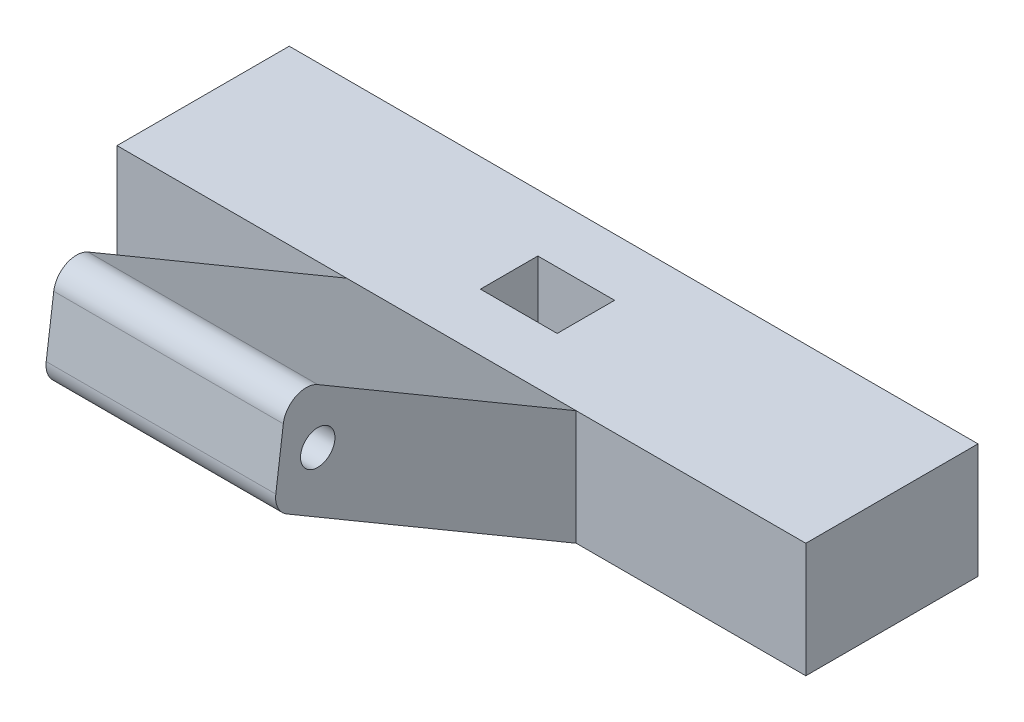
SolidWorks part; units mm, degrees
ref_plane "Plan de face" through (0, 0, 0) normal (0, 0, 1) x (1, 0, 0)
ref_plane "Plan de dessus" through (0, 0, 0) normal (0, 1, 0) x (1, 0, 0)
ref_plane "Plan de droite" through (0, 0, 0) normal (1, 0, 0) x (0, 0, -1)
sketch "Esquisse1" plane through (0, 0, 0) normal (0, 1, 0) x (1, 0, 0)
  line L6 (-30, -7.5) -> (30, -7.5)
  line L7 (-30, -7.5) -> (-30, 7.5)
  line L8 (-30, 7.5) -> (30, 7.5)
  line L9 (30, -7.5) -> (30, 7.5)
  line L10 (-30, -7.5) -> (30, 7.5) construction
  line L11 (-30, 7.5) -> (30, -7.5) construction
  circle A0 centre (0, 0) radius 3.6443
  point P2 (0, 0)
extrude "Boss.-Extru.2" add sketch "Esquisse1" along normal blind 10
sketch "Esquisse2" plane through (0, 0, 0) normal (1, 0, 0) x (0, 0, -1)
  line L0 (-7.5, 0) -> (-32.6999, 14.8076)
  line L1 (-7.5, 10) -> (-30.0164, 23.2308)
  line L2 (-33.6695, 16.7938) -> (-33.0124, 21.7683)
  line L3 (-7.5, 0) -> (-7.5, 10)
  arc A0 (-30.0164, 23.2308) -> (-33.0124, 21.7683) centre (-31.0296, 21.5064) ccw
  arc A1 (-33.6695, 16.7938) -> (-32.6999, 14.8076) centre (-31.6867, 16.5319) ccw
  circle A2 centre (-30.0164, 18.484) radius 1.5
  dimension "D1" = 2
extrude "Boss.-Extru.3" add sketch "Esquisse2" along normal blind 10 and the other way blind 10
sketch "Esquisse3" plane through (0, 10, 0) normal (0, 1, 0) x (1, 0, 0)
  line L1 (-3.3428, -2.5) -> (3.3428, -2.5)
  line L2 (-3.3428, -2.5) -> (-3.3428, 2.5)
  line L3 (-3.3428, 2.5) -> (3.3428, 2.5)
  line L4 (3.3428, -2.5) -> (3.3428, 2.5)
  line L5 (-3.3428, -2.5) -> (3.3428, 2.5) construction
  line L6 (-3.3428, 2.5) -> (3.3428, -2.5) construction
  point P0 (0, 0)
extrude "Enlèv. mat.-Extru.1" cut sketch "Esquisse3" against normal blind 10
sketch "Esquisse4" plane through (0, 10, 0) normal (0, 1, 0) x (1, 0, 0)
  line L0 (-2.6516, 2.5) -> (2.6516, 2.5)
  line L1 (2.6516, 2.5) -> (-0.9015, 6.6137)
  line L2 (-0.9015, 6.6137) -> (-2.6516, 2.5)
  line L3 (-3.3428, 1.4514) -> (-3.3428, -1.4514)
  line L4 (-3.3428, -1.4514) -> (-3.9842, -1.2297)
  line L5 (-3.9842, -1.2297) -> (-3.6635, 1.4514)
  line L6 (-3.6635, 1.4514) -> (-3.3428, 1.4514)
  line L7 (3.3428, 1.4514) -> (3.3428, -1.4514)
  line L8 (3.3428, -1.4514) -> (4.4476, -1.2297)
  line L9 (4.4476, -1.2297) -> (3.9712, 1.1443)
  line L10 (3.9712, 1.1443) -> (3.3428, 1.4514)
  line L11 (2.6516, -2.5) -> (-2.6516, -2.5)
  line L12 (-2.6516, -2.5) -> (-2.3713, -3.8969)
  line L13 (-2.3713, -3.8969) -> (1.6613, -4.0711)
  line L14 (1.6613, -4.0711) -> (2.6516, -2.5)
extrude "Boss.-Extru.5" add sketch "Esquisse4" against normal blind 10
